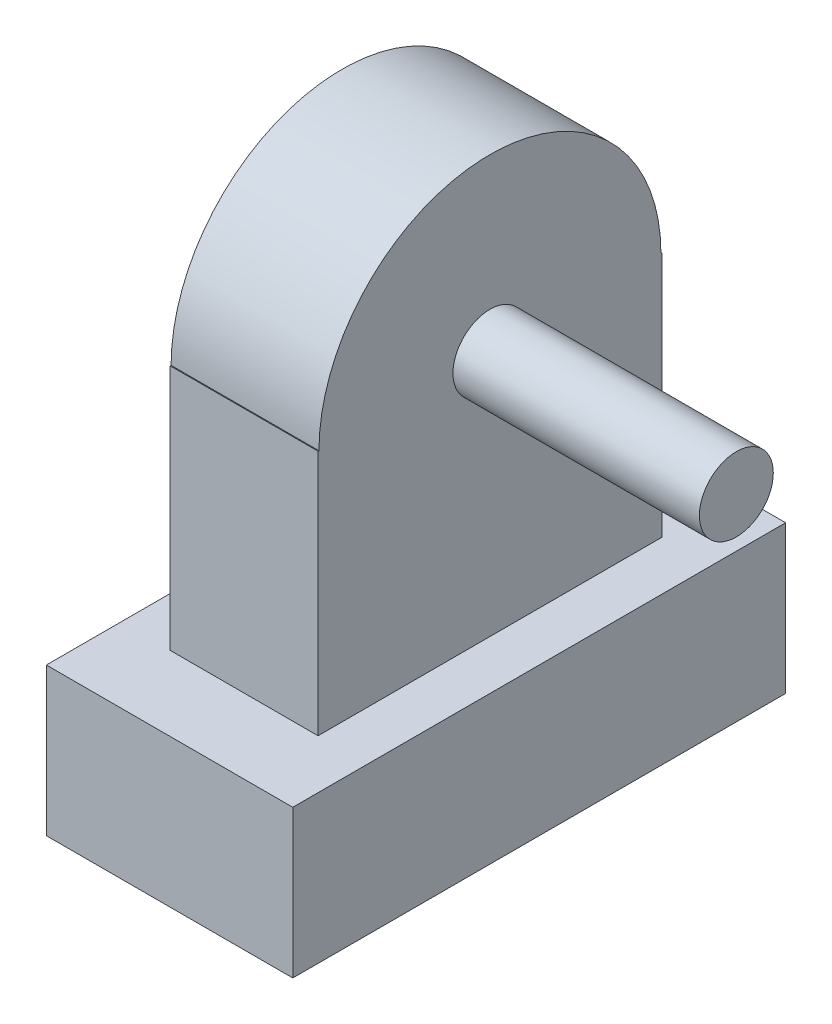
SolidWorks part; units mm, degrees
ref_plane "Front Plane" through (0, 0, 0) normal (0, 0, 1) x (1, 0, 0)
ref_plane "Top Plane" through (0, 0, 0) normal (0, 1, 0) x (1, 0, 0)
ref_plane "Right Plane" through (0, 0, 0) normal (1, 0, 0) x (0, 0, -1)
sketch "Sketch1" plane through (0, 0, 0) normal (0, 1, 0) x (1, 0, 0)
  line L1 (-25, 50) -> (25, 50)
  line L2 (-25, 50) -> (-25, -50)
  line L3 (-25, -50) -> (25, -50)
  line L4 (25, 50) -> (25, -50)
  line L5 (-25, 50) -> (25, -50) construction
  line L6 (-25, -50) -> (25, 50) construction
  point P0 (0, 0)
  dimension "D1" = 100
  dimension "D2" = 50
extrude "Boss-Extrude1" add sketch "Sketch1" along normal blind 30
sketch "Sketch3" plane through (0, 30, 0) normal (0, 1, 0) x (1, 0, 0)
  line L1 (-15, 34.871) -> (15, 34.871)
  line L2 (-15, 34.871) -> (-15, -34.871)
  line L3 (-15, -34.871) -> (15, -34.871)
  line L4 (15, 34.871) -> (15, -34.871)
  line L5 (-15, 34.871) -> (15, -34.871) construction
  line L6 (-15, -34.871) -> (15, 34.871) construction
  point P0 (0, 0)
  dimension "D1" = 30
extrude "Boss-Extrude2" add sketch "Sketch3" along normal blind 50
sketch "Sketch4" plane through (15, 0, 0) normal (1, 0, 0) x (0, 0, -1)
  line L0 (-34.871, 80) -> (34.871, 80) construction
  circle A0 centre (0, 80) radius 34.6934
extrude "Boss-Extrude3" add sketch "Sketch4" against normal blind 30
sketch "Sketch6" plane through (15, 0, 0) normal (1, 0, 0) x (0, 0, -1)
  circle A0 centre (0, 80) radius 7.5
  dimension "D1" = 15
extrude "Boss-Extrude4" add sketch "Sketch6" along normal blind 50
